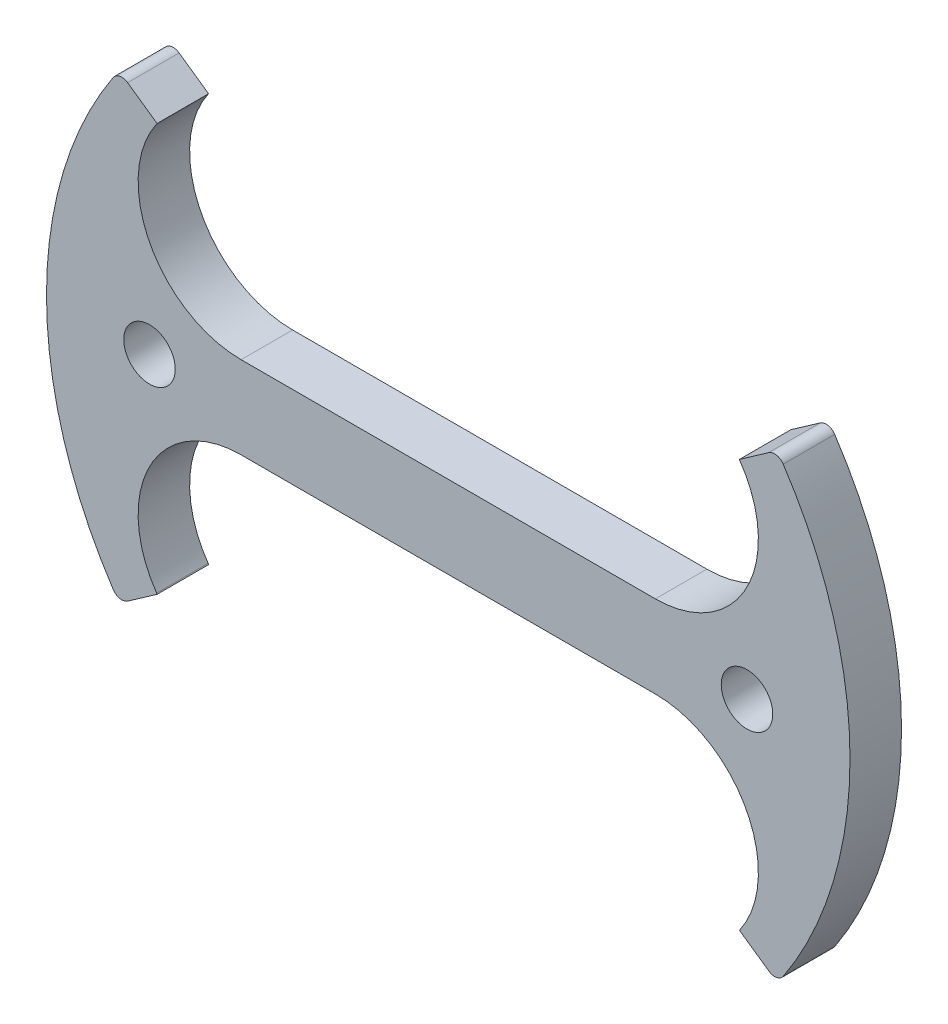
SolidWorks part; units mm, degrees
material "6061-T6 (SS)"
ref_plane "Front Plane" through (0, 0, 0) normal (0, 0, 1) x (1, 0, 0)
ref_plane "Top Plane" through (0, 0, 0) normal (0, 1, 0) x (1, 0, 0)
ref_plane "Right Plane" through (0, 0, 0) normal (1, 0, 0) x (0, 0, -1)
sketch "Sketch1" plane through (0, 0, 0) normal (0, 0, 1) x (1, 0, 0)
  line L0 (-43.5195, 5.08) -> (43.5195, 5.08)
  line L4 (-43.5195, -5.08) -> (43.5195, -5.08)
  circle A0 centre (0, 0) radius 49.53
  arc A3 (-43.5195, -5.08) -> (43.5195, -5.08) centre (0, 0) ccw
  arc A4 (43.5195, 5.08) -> (-43.5195, 5.08) centre (0, 0) ccw
  dimension "D1" = 99.06
  dimension "D2" = 87.63
  dimension "D3" = 5.08
extrude "Boss-Extrude2" add sketch "Sketch1" along normal blind 6.35
fillet "Fillet2" radius 12.7 1 edges at (43.5195, 5.08, 3.175)
fillet "Fillet3" radius 12.7 1 edges at (-43.5195, 5.08, 3.175)
fillet "Fillet4" radius 12.7 1 edges at (43.5195, -5.08, 3.175)
fillet "Fillet5" radius 12.7 1 edges at (-43.5195, -5.08, 3.175)
sketch "Sketch2" plane through (0, 0, 0) normal (0, 0, -1) x (-1, 0, 0)
  line L0 (-40.581, -28.3972) -> (-35.8986, -25.1206)
  line L1 (-40.5642, 28.4213) -> (-35.8837, 25.1419)
  line L2 (35.8837, -25.1419) -> (40.5642, -28.4213)
  line L3 (35.8986, 25.1206) -> (40.581, 28.3972)
  line L4 (-25.5346, -5.08) -> (25.5346, -5.08) construction
  circle A0 centre (0, 0) radius 49.53 construction
  arc A1 (-40.581, -28.3972) -> (40.5642, -28.4213) centre (0, 0) ccw
  arc A2 (40.581, 28.3972) -> (-40.5642, 28.4213) centre (0, 0) ccw
  arc A3 (35.8837, -25.1419) -> (-35.8986, -25.1206) centre (0, 0) cw
  arc A4 (-35.9569, -25.0371) -> (35.9569, -25.0371) centre (0, 0) ccw construction
  arc A5 (-35.8837, 25.1419) -> (35.8986, 25.1206) centre (0, 0) cw
  arc A6 (35.9569, 25.0371) -> (-35.9569, 25.0371) centre (0, 0) ccw construction
  point P4 (0, 0)
  point P6 (0, 0)
  point P8 (0, 0)
  point P9 (0, 0)
  point P10 (0, 0)
  point P11 (0, 0)
  point P16 (0, 0)
  dimension "D1" = 70
  dimension "D2" = 4.6073
extrude "Cut-Extrude1" cut sketch "Sketch2" against normal blind 6.35
sketch "Sketch3" plane through (0, 0, 0) normal (0, 0, -1) x (-1, 0, 0)
  circle A0 centre (-36.83, 0) radius 3.175
  circle A2 centre (36.83, 0) radius 3.175
  dimension "D1" = 6.35
  dimension "D2" = 36.83
  dimension "D3" = 36.83
extrude "Cut-Extrude2" cut sketch "Sketch3" against normal blind 6.35
fillet "Fillet6" radius 1.27 1 edges at (-40.581, 28.3972, 3.175)
fillet "Fillet7" radius 1.27 1 edges at (-40.5642, -28.4213, 3.175)
fillet "Fillet8" radius 1.27 1 edges at (40.581, -28.3972, 3.175)
fillet "Fillet9" radius 1.27 1 edges at (40.5642, 28.4213, 3.175)
